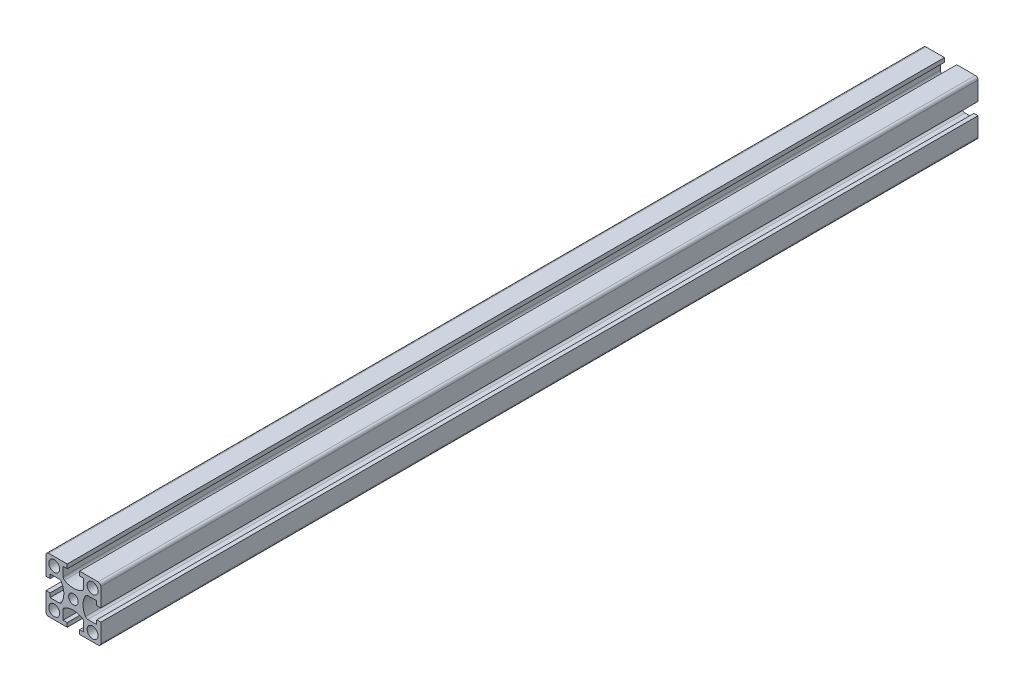
SolidWorks part; units mm, degrees
ref_plane "Front Plane" through (0, 0, 0) normal (0, 0, 1) x (1, 0, 0)
ref_plane "Top Plane" through (0, 0, 0) normal (0, 1, 0) x (1, 0, 0)
ref_plane "Right Plane" through (0, 0, 0) normal (1, 0, 0) x (0, 0, -1)
sketch "Sketch1" plane through (0, 0, 0) normal (0, 0, 1) x (1, 0, 0)
  line L64 (-12.5, 11.25) -> (-12.5, 2.8125)
  line L65 (-12.5, 2.8125) -> (-10.625, 2.8125)
  line L66 (-10.625, 2.8125) -> (-10.625, 4.6875)
  line L67 (-10.625, 4.6875) -> (-6.5461, 4.6875)
  line L68 (-6.5461, -4.6875) -> (-10.625, -4.6875)
  line L69 (-10.625, -4.6875) -> (-10.625, -2.8125)
  line L70 (-10.625, -2.8125) -> (-12.5, -2.8125)
  line L71 (-12.5, -2.8125) -> (-12.5, -11.25)
  line L72 (-11.25, -12.5) -> (-2.8125, -12.5)
  line L73 (-2.8125, -12.5) -> (-2.8125, -10.625)
  line L74 (-2.8125, -10.625) -> (-4.6875, -10.625)
  line L75 (-4.6875, -10.625) -> (-4.6875, -6.5461)
  line L76 (4.6875, -6.5461) -> (4.6875, -10.625)
  line L77 (4.6875, -10.625) -> (2.8125, -10.625)
  line L78 (2.8125, -10.625) -> (2.8125, -12.5)
  line L79 (2.8125, -12.5) -> (11.25, -12.5)
  line L80 (12.5, -11.25) -> (12.5, -2.8125)
  line L81 (12.5, -2.8125) -> (10.625, -2.8125)
  line L82 (10.625, -2.8125) -> (10.625, -4.6875)
  line L83 (10.625, -4.6875) -> (6.5461, -4.6875)
  line L84 (6.5461, 4.6875) -> (10.625, 4.6875)
  line L85 (10.625, 4.6875) -> (10.625, 2.8125)
  line L86 (10.625, 2.8125) -> (12.5, 2.8125)
  line L87 (12.5, 2.8125) -> (12.5, 11.25)
  line L88 (11.25, 12.5) -> (2.8125, 12.5)
  line L89 (2.8125, 12.5) -> (2.8125, 10.625)
  line L90 (2.8125, 10.625) -> (4.6875, 10.625)
  line L91 (4.6875, 10.625) -> (4.6875, 6.5461)
  line L92 (-4.6875, 6.5461) -> (-4.6875, 10.625)
  line L93 (-4.6875, 10.625) -> (-2.8125, 10.625)
  line L94 (-2.8125, 10.625) -> (-2.8125, 12.5)
  line L95 (-2.8125, 12.5) -> (-11.25, 12.5)
  circle A5 centre (-8.75, -8.75) radius 2.5
  circle A6 centre (8.75, -8.75) radius 2.5
  circle A7 centre (8.75, 8.75) radius 2.5
  circle A8 centre (0, 0) radius 2.1875
  circle A9 centre (-8.75, 8.75) radius 2.5
  arc A32 (-11.25, 12.5) -> (-12.5, 11.25) centre (-11.25, 11.25) ccw
  arc A33 (-5.4635, 4.0625) -> (-6.5461, 4.6875) centre (-6.5461, 3.4375) ccw
  arc A34 (-5.4635, -4.0625) -> (-5.4635, 4.0625) centre (-12.5, 0) ccw
  arc A35 (-6.5461, -4.6875) -> (-5.4635, -4.0625) centre (-6.5461, -3.4375) ccw
  arc A36 (-12.5, -11.25) -> (-11.25, -12.5) centre (-11.25, -11.25) ccw
  arc A37 (-4.0625, -5.4635) -> (-4.6875, -6.5461) centre (-3.4375, -6.5461) ccw
  arc A38 (4.0625, -5.4635) -> (-4.0625, -5.4635) centre (0, -12.5) ccw
  arc A39 (4.6875, -6.5461) -> (4.0625, -5.4635) centre (3.4375, -6.5461) ccw
  arc A40 (11.25, -12.5) -> (12.5, -11.25) centre (11.25, -11.25) ccw
  arc A41 (5.4635, -4.0625) -> (6.5461, -4.6875) centre (6.5461, -3.4375) ccw
  arc A42 (5.4635, 4.0625) -> (5.4635, -4.0625) centre (12.5, 0) ccw
  arc A43 (6.5461, 4.6875) -> (5.4635, 4.0625) centre (6.5461, 3.4375) ccw
  arc A44 (12.5, 11.25) -> (11.25, 12.5) centre (11.25, 11.25) ccw
  arc A45 (4.0625, 5.4635) -> (4.6875, 6.5461) centre (3.4375, 6.5461) ccw
  arc A46 (-4.0625, 5.4635) -> (4.0625, 5.4635) centre (0, 12.5) ccw
  arc A47 (-4.6875, 6.5461) -> (-4.0625, 5.4635) centre (-3.4375, 6.5461) ccw
extrude "Boss-Extrude1" add sketch "Sketch1" along normal blind 400
